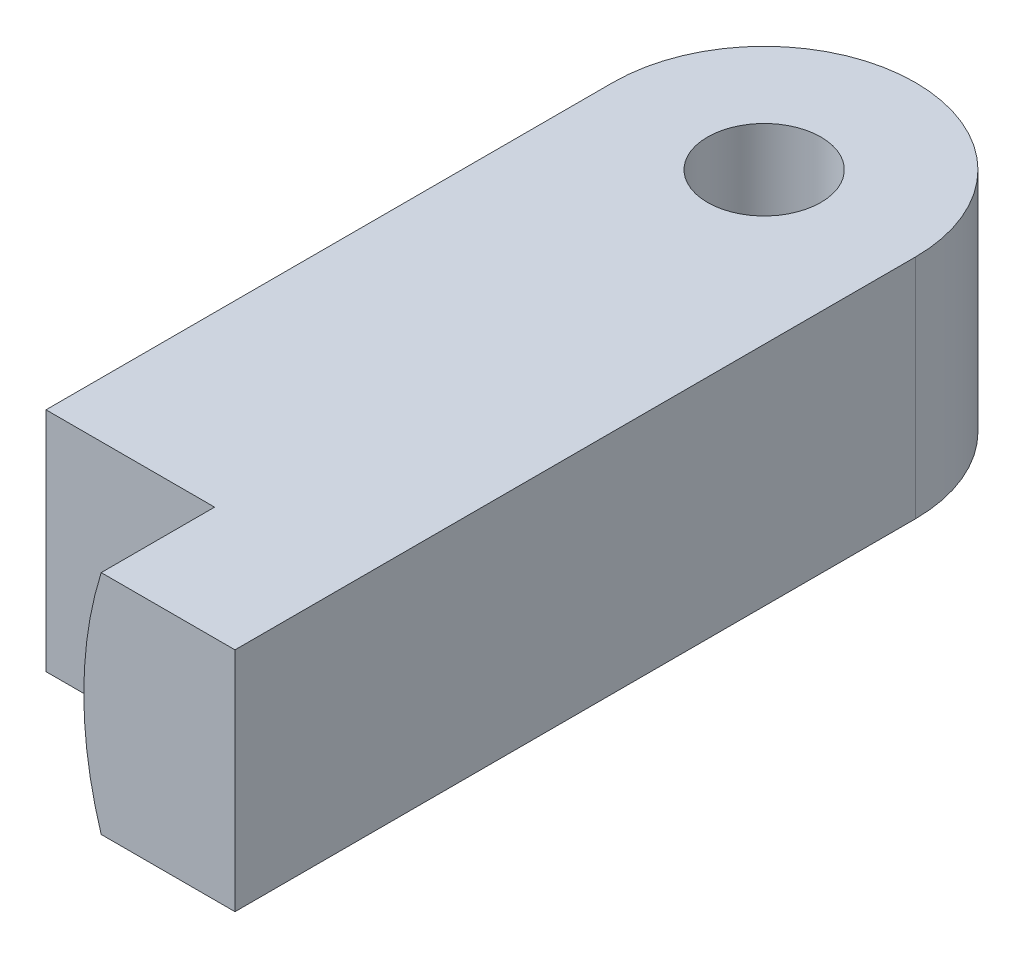
SolidWorks part; units mm, degrees
material "ABS"
ref_plane "Alzado" through (0, 0, 0) normal (0, 0, 1) x (1, 0, 0)
ref_plane "Planta" through (0, 0, 0) normal (0, 1, 0) x (1, 0, 0)
ref_plane "Vista lateral" through (0, 0, 0) normal (1, 0, 0) x (0, 0, -1)
sketch "Croquis1" plane through (0, 0, 0) normal (0, 0, 1) x (1, 0, 0)
  line L1 (-4, 3) -> (4, 3)
  line L2 (-4, 3) -> (-4, -3)
  line L3 (-4, -3) -> (4, -3)
  line L4 (4, 3) -> (4, -3)
  line L5 (-4, 3) -> (4, -3) construction
  line L6 (-4, -3) -> (4, 3) construction
  point P0 (0, 0)
  dimension "D1" = 6
  dimension "D2" = 8
extrude "Saliente-Extruir1" add sketch "Croquis1" along normal blind 25
sketch "Croquis2" plane through (0, 3, 0) normal (0, 1, 0) x (1, 0, 0)
  line L1 (-4, -25) -> (0, -25)
  line L2 (-4, -25) -> (-4, -22)
  line L3 (-4, -22) -> (0, -22)
  line L4 (0, -25) -> (0, -22)
  dimension "D1" = 3
extrude "Cortar-Extruir1" cut sketch "Croquis2" against normal through all contours L2 L1 L4 L3
sketch "Croquis3" plane through (0, -3, 0) normal (0, -1, 0) x (1, 0, 0)
  circle A0 centre (0, 7) radius 1.5
  dimension "D2" = 3
  dimension "D1" = 18
extrude "Cortar-Extruir2" cut sketch "Croquis3" against normal blind 3
sketch "Croquis4" plane through (0, -3, 0) normal (0, -1, 0) x (1, 0, 0)
  circle A0 centre (0, 7) radius 4
  circle A1 centre (0, 7) radius 1.5
  dimension "D1" = 8
extrude "Saliente-Extruir2" add sketch "Croquis4" against normal blind 3
sketch "Croquis5" plane through (0, 3, 0) normal (0, 1, 0) x (1, 0, 0)
  line L0 (4, -25) -> (4, -13)
  line L1 (4, -25) -> (4, 0) construction
  line L3 (-4, 0) -> (4, 0)
  line L4 (-4, 0) -> (-4, -7)
  line L5 (-4, -7) -> (4, -7)
  line L6 (4, 0) -> (4, -7)
  circle A0 centre (0, -7) radius 1.5
  circle A1 centre (0, -7) radius 4
  line M9 (4, -25) -> (4, 0)
  line M10 (4, 0) -> (-4, 0)
  line M11 (-4, 0) -> (-4, -22)
  dimension "D2" = 3
  dimension "D1" = 12
  dimension "D3" = 6
extrude "Cortar-Extruir3" cut sketch "Croquis5" against normal through all contours A1 M9 M10 M11 | L5 A0 | L5 A0
sketch "Croquis6" plane through (0, 0, 25) normal (0, 0, 1) x (1, 0, 0)
  line L2 (0, -3) -> (4, -3)
  line L3 (0, -3) -> (0, 3)
  line L4 (0, 3) -> (4, 3)
  line L5 (4, -3) -> (4, 3)
  circle A0 centre (10, 0) radius 10
  line M2 (0, 3) -> (0, -3)
  line M3 (0, -3) -> (4, -3)
  dimension "D1" = 20
extrude "Cortar-Extruir4" cut sketch "Croquis6" against normal blind 3 contours A0 L4 M2 | A0 L3 M3
